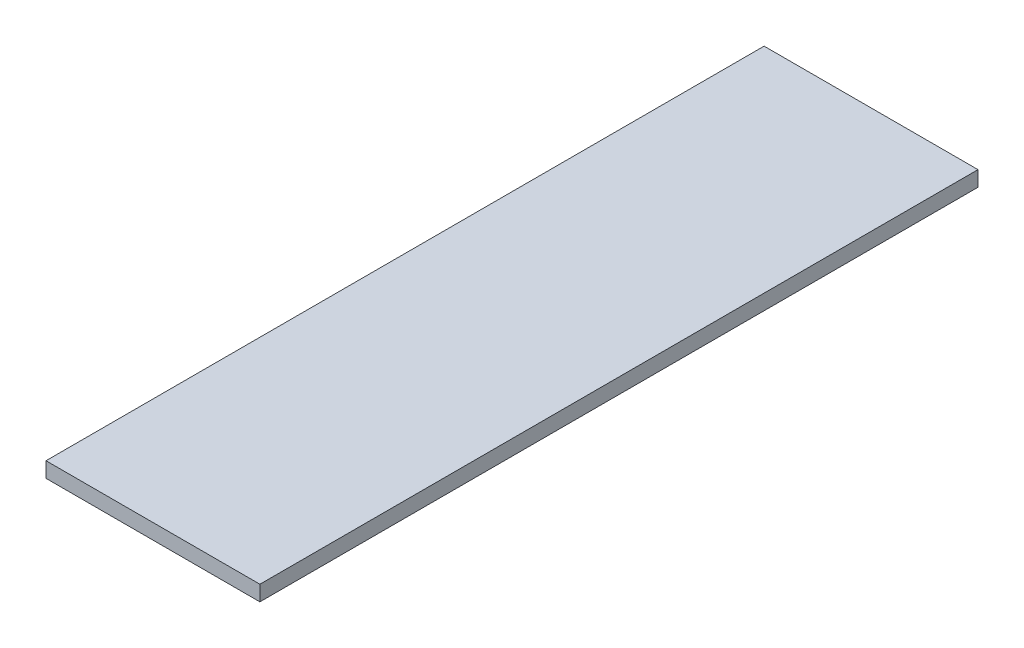
SolidWorks part; units mm, degrees
material "Бетон М200"
ref_plane "Спереди" through (0, 0, 0) normal (0, 0, 1) x (1, 0, 0)
ref_plane "Сверху" through (0, 0, 0) normal (0, 1, 0) x (1, 0, 0)
ref_plane "Справа" through (0, 0, 0) normal (1, 0, 0) x (0, 0, -1)
sketch "Эскиз1" plane through (0, 0, 0) normal (0, 1, 0) x (1, 0, 0)
  line L0 (-900, 0) -> (-900, -2380) construction
  line L1 (-1050, 150) -> (1050, 150)
  line L2 (-1050, 150) -> (-1050, -6900)
  line L3 (-1050, -6900) -> (1050, -6900)
  line L4 (1050, 150) -> (1050, -6900)
  line L5 (900, 0) -> (-300, 0) construction
  line L7 (-740, -6750) -> (740, -6750) construction
  point P4 (0, 150)
  dimension "D1" = 150
  dimension "D2" = 150
  dimension "D3" = 150
extrude "Бобышка-Вытянуть1" add sketch "Эскиз1" against normal blind 150
sketch "Эскиз2" plane through (0, 0, 0) normal (0, 1, 0) x (1, 0, 0)
  line L0 (-1050, -6900) -> (1050, -6900) construction
  line L1 (-400, -6900) -> (400, -6900)
  line L2 (-400, -6900) -> (-400, -5050)
  line L3 (-400, -5050) -> (400, -5050)
  line L4 (400, -6900) -> (400, -5050)
  line L5 (-500, -4900) -> (500, -4900) construction
  line L6 (-500, -4900) -> (-500, -6550) construction
  line L7 (500, -6550) -> (500, -4900) construction
  dimension "D1" = 150
  dimension "D2" = 100
  dimension "D3" = 100
extrude "Вырез-Вытянуть1" [suppressed] cut sketch "Эскиз2" against normal through all
